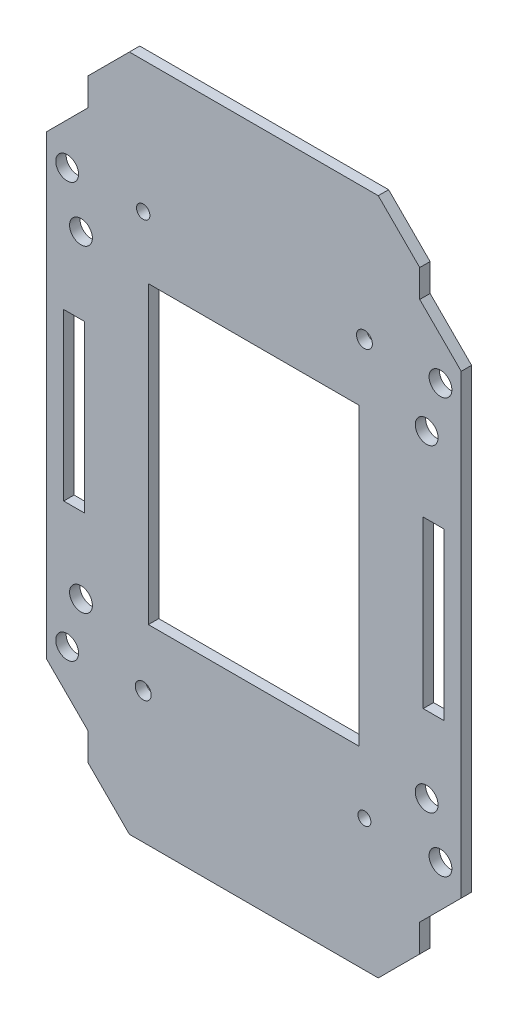
SolidWorks part; units mm, degrees
material "碳纤维板_1600kg_m3"
ref_plane "前视基准面" through (0, 0, 0) normal (0, 0, 1) x (1, 0, 0)
ref_plane "上视基准面" through (0, 0, 0) normal (0, 1, 0) x (1, 0, 0)
ref_plane "右视基准面" through (0, 0, 0) normal (1, 0, 0) x (0, 0, -1)
other "Configuration Table"
sketch "草图1" plane through (0, 0, 0) normal (0, 0, 1) x (1, 0, 0)
  line L0 (14.7991, -21.3549) -> (15.6991, -21.3549) construction
  line L1 (-15.2491, 21.3549) -> (15.2491, 21.3549)
  line L2 (-15.2491, 21.3549) -> (-15.2491, -21.3549)
  line L3 (-15.2491, -21.3549) -> (15.2491, -21.3549)
  line L4 (15.2491, 21.3549) -> (15.2491, -21.3549)
  line L5 (-15.2491, 21.3549) -> (15.2491, -21.3549) construction
  line L6 (-15.2491, -21.3549) -> (15.2491, 21.3549) construction
  line L32 (24, -39) -> (24, -43)
  line L33 (24, -43) -> (18, -49)
  line L34 (18, -49) -> (-18, -49)
  line L35 (-18, -49) -> (-24, -43)
  line L36 (-24, -43) -> (-24, -39)
  line L37 (-24, -39) -> (-30, -33)
  line L38 (-30, -33) -> (-30, 33)
  line L39 (-30, 33) -> (-24, 39)
  line L40 (-24, 39) -> (-24, 43)
  line L41 (-24, 43) -> (-18, 49)
  line L42 (-18, 49) -> (18, 49)
  line L43 (18, 49) -> (24, 43)
  line L44 (24, 43) -> (24, 39)
  line L45 (24, 39) -> (30, 33)
  line L46 (30, 33) -> (30, -33)
  line L47 (30, -33) -> (24, -39)
  line L48 (-27.5, -12) -> (-24.5, -12)
  line L49 (-24.5, -12) -> (-24.5, 12)
  line L50 (-24.5, 12) -> (-27.5, 12)
  line L51 (-27.5, 12) -> (-27.5, -12)
  line L52 (24.5, -12) -> (27.5, -12)
  line L53 (27.5, -12) -> (27.5, 12)
  line L54 (27.5, 12) -> (24.5, 12)
  line L55 (24.5, 12) -> (24.5, -12)
  circle A0 centre (16, 30) radius 1.15
  circle A1 centre (-16, -30) radius 1.15
  circle A2 centre (16, -30) radius 0.94
  circle A3 centre (-16, 30) radius 0.9677
  circle A12 centre (-27, -30) radius 1.65
  circle A13 centre (-27, 30) radius 1.65
  circle A14 centre (27, -30) radius 1.65
  circle A15 centre (27, 30) radius 1.65
  point P8 (0, 0)
extrude "Pixhawk正装减振托板_绑带槽_四M3孔" add sketch "草图1" along normal blind 1.5
sketch "草图2" plane through (0, 0, 0) normal (0, 0, 1) x (1, 0, 0)
  circle A0 centre (-25, -23) radius 1.65
  circle A1 centre (-25, 23) radius 1.65
  circle A2 centre (25, -23) radius 1.65
  circle A3 centre (25, 23) radius 1.65
extrude "电调叠装框四孔" cut sketch "草图2" along normal blind 1.5
